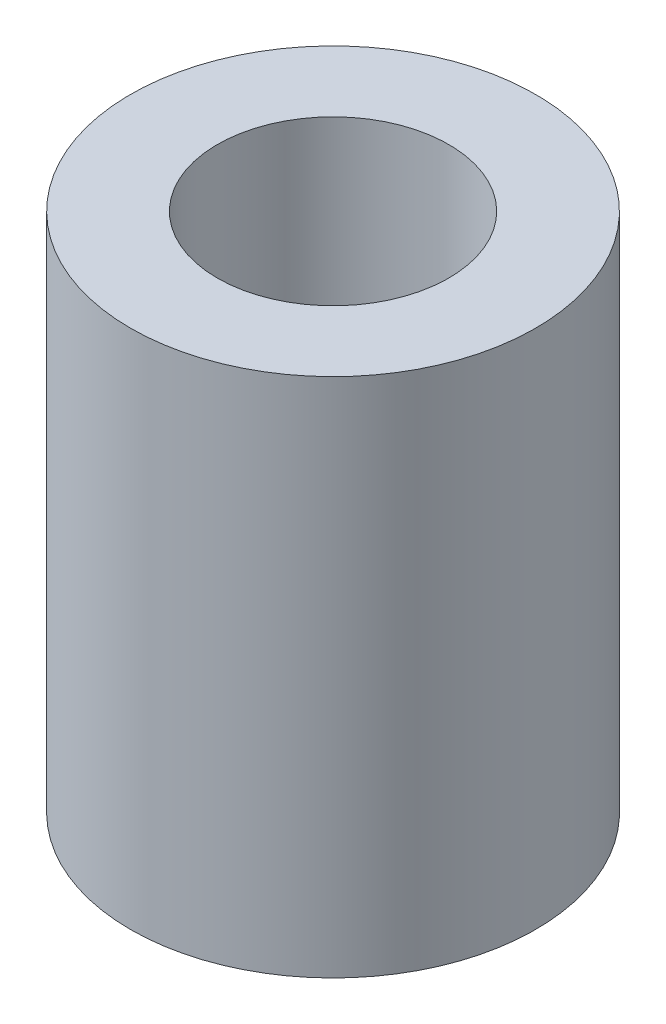
SolidWorks part; units mm, degrees
ref_plane "Front Plane" through (0, 0, 0) normal (0, 0, 1) x (1, 0, 0)
ref_plane "Top Plane" through (0, 0, 0) normal (0, 1, 0) x (1, 0, 0)
ref_plane "Right Plane" through (0, 0, 0) normal (1, 0, 0) x (0, 0, -1)
sketch "Sketch1" plane through (0, 0, 0) normal (0, 1, 0) x (1, 0, 0)
  circle A0 centre (0, 0) radius 2.54
  circle A1 centre (0, 0) radius 4.445
  dimension "D1" = 5.08
  dimension "D2" = 8.89
extrude "Boss-Extrude1" add sketch "Sketch1" along normal blind 11.43
